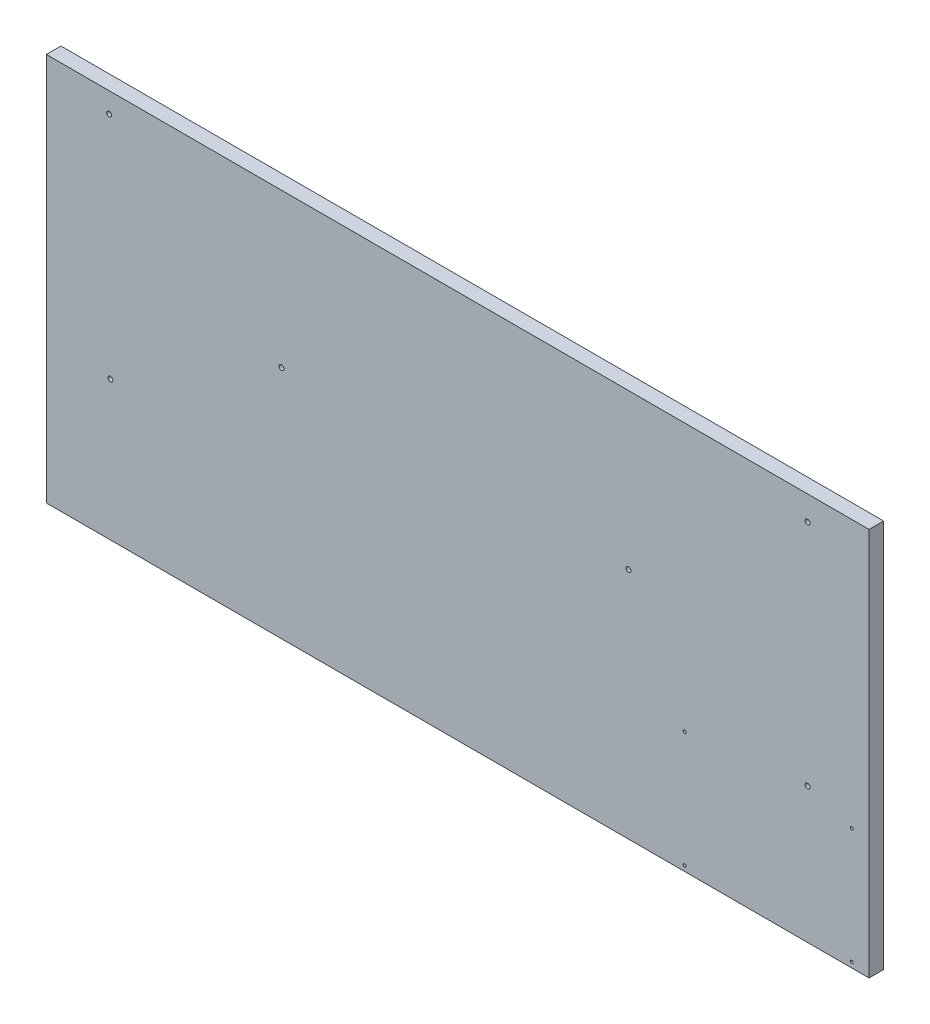
SolidWorks part; units mm, degrees
ref_plane "Plano frontal" through (0, 0, 0) normal (0, 0, 1) x (1, 0, 0)
ref_plane "Plano superior" through (0, 0, 0) normal (0, 1, 0) x (1, 0, 0)
ref_plane "Plano direito" through (0, 0, 0) normal (1, 0, 0) x (0, 0, -1)
sketch "Esboço1" plane through (0, 0, 0) normal (0, 0, 1) x (1, 0, 0)
  line L1 (422.5, -199.5) -> (-422.5, -199.5)
  line L2 (422.5, -199.5) -> (422.5, 199.5)
  line L3 (422.5, 199.5) -> (-422.5, 199.5)
  line L4 (-422.5, -199.5) -> (-422.5, 199.5)
  line L5 (422.5, -199.5) -> (-422.5, 199.5) construction
  line L6 (422.5, 199.5) -> (-422.5, -199.5) construction
  point P0 (0, 0)
  dimension "D1" = 399
  dimension "D2" = 845
extrude "Ressalto-extrusão1" add sketch "Esboço1" along normal blind 15
sketch "Esboço2" plane through (0, 0, 15) normal (0, 0, 1) x (1, 0, 0)
  line L0 (-422.5, 199.5) -> (-422.5, -199.5) construction
  line L1 (422.5, 199.5) -> (-422.5, 199.5) construction
  line L2 (-422.5, -199.5) -> (422.5, -199.5) construction
  line L3 (422.5, -199.5) -> (422.5, 199.5) construction
  circle A0 centre (-358, 178.7) radius 2.5
  circle A1 centre (-356.7, -56.3) radius 2.5
  circle A2 centre (-181, 41.7) radius 2.5
  circle A3 centre (359.4, -60.3) radius 2.5
  circle A4 centre (359.4, 174.5) radius 2.5
  circle A5 centre (175.4, 40.3) radius 2.5
  dimension "D3" = 5
  dimension "D6" = 5
  dimension "D9" = 5
  dimension "D12" = 5
  dimension "D15" = 5
  dimension "D18" = 5
  dimension "D1" = 64.5
  dimension "D2" = 20.8
  dimension "D4" = 65.8
  dimension "D5" = 143.2
  dimension "D7" = 241.2
  dimension "D8" = 241.5
  dimension "D10" = 63.1
  dimension "D11" = 139.2
  dimension "D13" = 63.1
  dimension "D14" = 25
  dimension "D16" = 247.1
  dimension "D17" = 159.2
extrude "Corte-extrusão1" cut sketch "Esboço2" against normal blind 10
sketch "Esboço3" plane through (0, 0, 15) normal (0, 0, 1) x (1, 0, 0)
  line L0 (-422.5, -199.5) -> (422.5, -199.5) construction
  line L1 (422.5, -199.5) -> (422.5, 199.5) construction
  circle A0 centre (233, -75.1) radius 1.5
  circle A1 centre (404.7, -75.1) radius 1.5
  dimension "D2" = 3
  dimension "D5" = 3
  dimension "D1" = 124.4
  dimension "D3" = 189.5
  dimension "D4" = 17.8
extrude "Corte-extrusão2" cut sketch "Esboço3" against normal blind 10
sketch "Esboço4" plane through (0, 0, 15) normal (0, 0, 1) x (1, 0, 0)
  line L0 (-422.5, -199.5) -> (422.5, -199.5) construction
  line L1 (422.5, -199.5) -> (422.5, 199.5) construction
  circle A0 centre (233, -194.1) radius 1.5
  circle A2 centre (404.7, -194.1) radius 1.5
  dimension "D2" = 189.5
  dimension "D3" = 3
  dimension "D6" = 3
  dimension "D1" = 5.4
  dimension "D4" = 17.8
  dimension "D5" = 5.4
extrude "Corte-extrusão3" cut sketch "Esboço4" against normal through all
